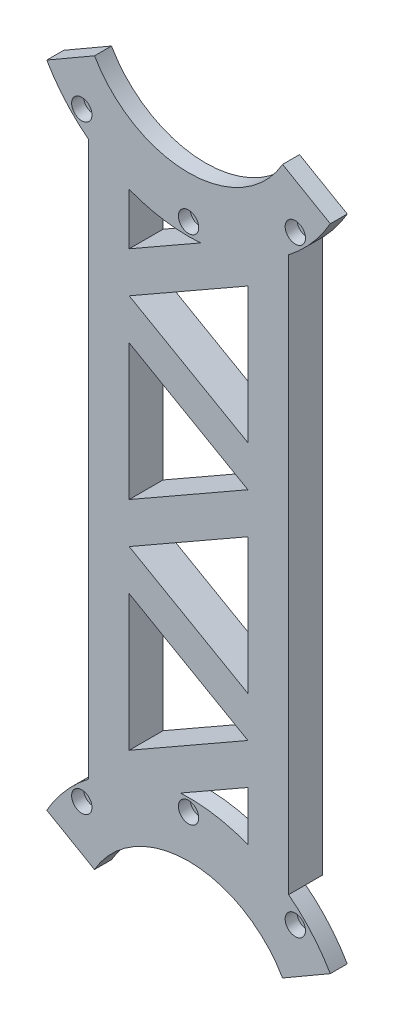
SolidWorks part; units mm, degrees
ref_plane "Front Plane" through (0, 0, 0) normal (0, 0, 1) x (1, 0, 0)
ref_plane "Top Plane" through (0, 0, 0) normal (0, 1, 0) x (1, 0, 0)
ref_plane "Right Plane" through (0, 0, 0) normal (1, 0, 0) x (0, 0, -1)
sketch "Sketch1" plane through (0, 0, 0) normal (0, 0, 1) x (1, 0, 0)
  circle A0 centre (0, 0) radius 48.25
extrude "Boss-Extrude1" add sketch "Sketch1" against normal blind 10 contours A0
sketch "Sketch2" plane through (0, 0, 0) normal (0, 0, 1) x (1, 0, 0)
  line L1 (-63.412, 28.4111) -> (-46.25, 28.4111)
  line L2 (-63.412, 28.4111) -> (-63.412, -28.4111)
  line L3 (-63.412, -28.4111) -> (-46.25, -28.4111)
  line L4 (-46.25, 28.4111) -> (-46.25, -28.4111)
  line L5 (46.25, 28.4111) -> (62.4025, 28.4111)
  line L6 (46.25, 28.4111) -> (46.25, -36.7758)
  line L7 (46.25, -36.7758) -> (62.4025, -36.7758)
  line L8 (62.4025, 28.4111) -> (62.4025, -36.7758)
  dimension "D1" = 92.5
  dimension "D2" = 46.25
extrude "Cut-Extrude1" cut sketch "Sketch2" against normal blind 8 contours L5 L8 L7 L6 | L1 L4 L3 L2
sketch "Sketch3" plane through (0, 0, 0) normal (0, 0, 1) x (1, 0, 0)
  circle A0 centre (0, 0) radius 32
extrude "Cut-Extrude2" cut sketch "Sketch3" against normal blind 10 contours A0
sketch "Sketch4" plane through (0, 0, 0) normal (0, 0, 1) x (1, 0, 0)
  circle A0 centre (-42.5, 0) radius 1.75
  circle A1 centre (0, -44.5) radius 1.75
  circle A2 centre (0, 44.5) radius 1.75
  circle A3 centre (42.5, 0) radius 1.75
  circle A4 centre (-31.4663, -31.4663) radius 1.75
  circle A5 centre (31.4663, -31.4663) radius 1.75
  circle A6 centre (31.4663, 31.4663) radius 1.75
  circle A7 centre (-31.4663, 31.4663) radius 1.75
  point P10 (0, 0)
  point P13 (0, 0)
  point P16 (0, 0)
  point P19 (0, 0)
  point P22 (0, 0)
  point P25 (0, 0)
  dimension "D1" = 42.5
  dimension "D3" = 2
  dimension "D2" = 44.5
  dimension "D4" = 2
  dimension "D5" = 2
  dimension "D6" = 2
  dimension "D7" = 2
  dimension "D8" = 2
extrude "Cut-Extrude3" cut sketch "Sketch4" against normal blind 10
sketch "Sketch9" plane through (0, 0, 0) normal (0, 0, 1) x (1, 0, 0)
  circle A0 centre (-42.5, 0) radius 3
  circle A1 centre (42.5, 0) radius 3
  circle A2 centre (31.4663, 31.4663) radius 3
  circle A3 centre (-31.4663, 31.4663) radius 3
  circle A4 centre (-31.4663, -31.4663) radius 3
  circle A5 centre (31.4663, -31.4663) radius 3
  circle A6 centre (0, -44.5) radius 3
  circle A7 centre (0, 44.5) radius 3
sketch "Sketch10" plane through (0, 0, 0) normal (0, 0, 1) x (1, 0, 0)
  line L0 (0, 0) -> (0, 210) construction
  line L1 (-29.5, 0) -> (-29.5, 210)
  line L2 (29.5, 0) -> (29.5, 210)
  line L3 (-17.5, 39.54) -> (-17.5, 51.54)
  line L4 (-17.5, 215.0793) -> (17.5, 215.0793)
  line L5 (-17.5, 215.0793) -> (-17.5, -10.6365)
  line L6 (-17.5, -10.6365) -> (17.5, -10.6365)
  line L7 (17.5, 215.0793) -> (17.5, -10.6365)
  line L8 (-17.5, 39.54) -> (17.5, 59.54)
  line L9 (-17.5, 51.54) -> (17.5, 71.54)
  line L10 (17.5, 59.54) -> (17.5, 71.54)
  line L11 (17.5, 71.54) -> (17.5, 83.54)
  line L12 (17.5, 71.54) -> (-17.5, 91.54)
  line L13 (17.5, 83.54) -> (-17.5, 103.54)
  line L14 (-17.5, 91.54) -> (-17.5, 103.54)
  line L15 (-17.5, 103.54) -> (-17.5, 115.54)
  line L16 (-17.5, 103.54) -> (17.5, 123.54)
  line L17 (-17.5, 115.54) -> (17.5, 135.54)
  line L18 (17.5, 123.54) -> (17.5, 135.54)
  line L19 (17.5, 135.54) -> (17.5, 147.54)
  line L20 (17.5, 135.54) -> (-17.5, 155.54)
  line L21 (17.5, 147.54) -> (-17.5, 167.54)
  line L22 (-17.5, 155.54) -> (-17.5, 167.54)
  line L23 (-17.5, 167.54) -> (-17.5, 179.54)
  line L24 (-17.5, 167.54) -> (17.5, 187.54)
  line L25 (-17.5, 179.54) -> (17.5, 199.54)
  line L26 (17.5, 187.54) -> (17.5, 199.54)
  arc A0 (-29.5, 0) -> (29.5, 0) centre (0, 0) ccw
  arc A1 (29.5, 210) -> (-29.5, 210) centre (0, 210) ccw
  point P3 (0, 105)
  dimension "D1" = 12
  dimension "D2" = 12
  dimension "D3" = 12
  dimension "D4" = 20
  dimension "D5" = 12
  dimension "D6" = 20
  dimension "D7" = 12
  dimension "D8" = 20
  dimension "D9" = 12
  dimension "D10" = 20
  dimension "D11" = 12
  dimension "D12" = 20
extrude "Cut-Extrude4" cut sketch "Sketch9" against normal blind 3.5
sketch "Sketch12" plane through (0, 0, 0) normal (0, 0, 1) x (1, 0, 0)
  circle A0 centre (0, 239.6942) radius 48.25
  dimension "D1" = 0
extrude "Boss-Extrude4" add sketch "Sketch12" against normal blind 10 separate body contours A0
sketch "Sketch13" plane through (0, 0, 0) normal (0, 0, 1) x (1, 0, 0)
  line L1 (-63.412, 436.9676) -> (-46.25, 436.9676)
  line L2 (-63.412, 436.9676) -> (-63.412, 196.7016)
  line L3 (-63.412, 196.7016) -> (-46.25, 196.7016)
  line L4 (-46.25, 436.9676) -> (-46.25, 196.7016)
  line L5 (46.25, 187.19) -> (62.4025, 187.19)
  line L6 (46.25, 187.19) -> (46.25, 413.3722)
  line L7 (46.25, 413.3722) -> (62.4025, 413.3722)
  line L8 (62.4025, 187.19) -> (62.4025, 413.3722)
  dimension "D1" = 92.5
extrude "Cut-Extrude5" cut sketch "Sketch13" against normal blind 5
sketch "Sketch14" plane through (0, 0, 0) normal (0, 0, 1) x (1, 0, 0)
  circle A0 centre (0, 239.6942) radius 30
extrude "Cut-Extrude6" cut sketch "Sketch14" against normal blind 10 contours A0
sketch "Sketch17" plane through (0, 0, 0) normal (0, 0, 1) x (1, 0, 0)
  line L0 (0, 0) -> (-69.3043, 39.9614)
  line L1 (-69.3043, 39.9614) -> (-69.2783, -65.3223)
  line L2 (-69.2783, -65.3223) -> (63.9709, -62.4072)
  line L3 (63.9709, -62.4072) -> (69.2598, 40.0386)
  line L4 (69.2598, 40.0386) -> (0, 0)
  dimension "D1" = 120
  dimension "D2" = 80
  dimension "D3" = 80
extrude "Cut-Extrude7" cut sketch "Sketch17" against normal blind 10
sketch "Sketch18" plane through (0, 0, 0) normal (0, 0, 1) x (1, 0, 0)
  line L0 (0, 239.6942) -> (-69.2843, 199.698)
  line L1 (-69.2843, 199.698) -> (-69.0664, 357.5112)
  line L2 (-69.0664, 357.5112) -> (54.7017, 362.3334)
  line L3 (54.7017, 362.3334) -> (69.2798, 199.6903)
  line L4 (69.2798, 199.6903) -> (0, 239.6942)
  point P0 (69.2798, 199.698)
  dimension "D1" = 120
  dimension "D2" = 80
  dimension "D3" = 80
extrude "Cut-Extrude8" cut sketch "Sketch18" against normal blind 10
sketch "Sketch19" plane through (0, 0, 0) normal (0, 0, 1) x (1, 0, 0)
  line L0 (0, 0) -> (0, 210) construction
  circle A0 centre (0, 195.1942) radius 1.75
  circle A1 centre (0, 239.6942) radius 30 construction
  circle A2 centre (-31.4663, 208.2279) radius 1.75
  circle A3 centre (31.4663, 208.2279) radius 1.75
  point P12 (0, 239.6942)
  point P15 (0, 239.6942)
  dimension "D1" = 44.5
  dimension "D2" = 2
  dimension "D3" = 2
extrude "Cut-Extrude9" cut sketch "Sketch19" against normal blind 10
extrude "Boss-Extrude5" add sketch "Sketch10" against normal blind 10
sketch "Sketch21" plane through (0, 0, 0) normal (0, 0, 1) x (1, 0, 0)
  circle A0 centre (0, 239.6942) radius 32
extrude "Cut-Extrude11" cut sketch "Sketch21" against normal blind 10
sketch "Sketch23" plane through (0, 0, 0) normal (0, 0, 1) x (1, 0, 0)
  circle A0 centre (-31.4663, 208.2279) radius 3
  circle A1 centre (0, 195.1942) radius 3
  circle A2 centre (31.4663, 208.2279) radius 3
  circle A3 centre (0, 44.5) radius 3
extrude "Cut-Extrude13" cut sketch "Sketch23" against normal blind 3.5
sketch "Sketch24" plane through (0, 0, -10) normal (0, 0, -1) x (-1, 0, 0)
  circle A0 centre (0, 239.6942) radius 48.25
  circle A1 centre (0, 0) radius 48.25
extrude "Cut-Extrude14" cut sketch "Sketch24" against normal blind 5
